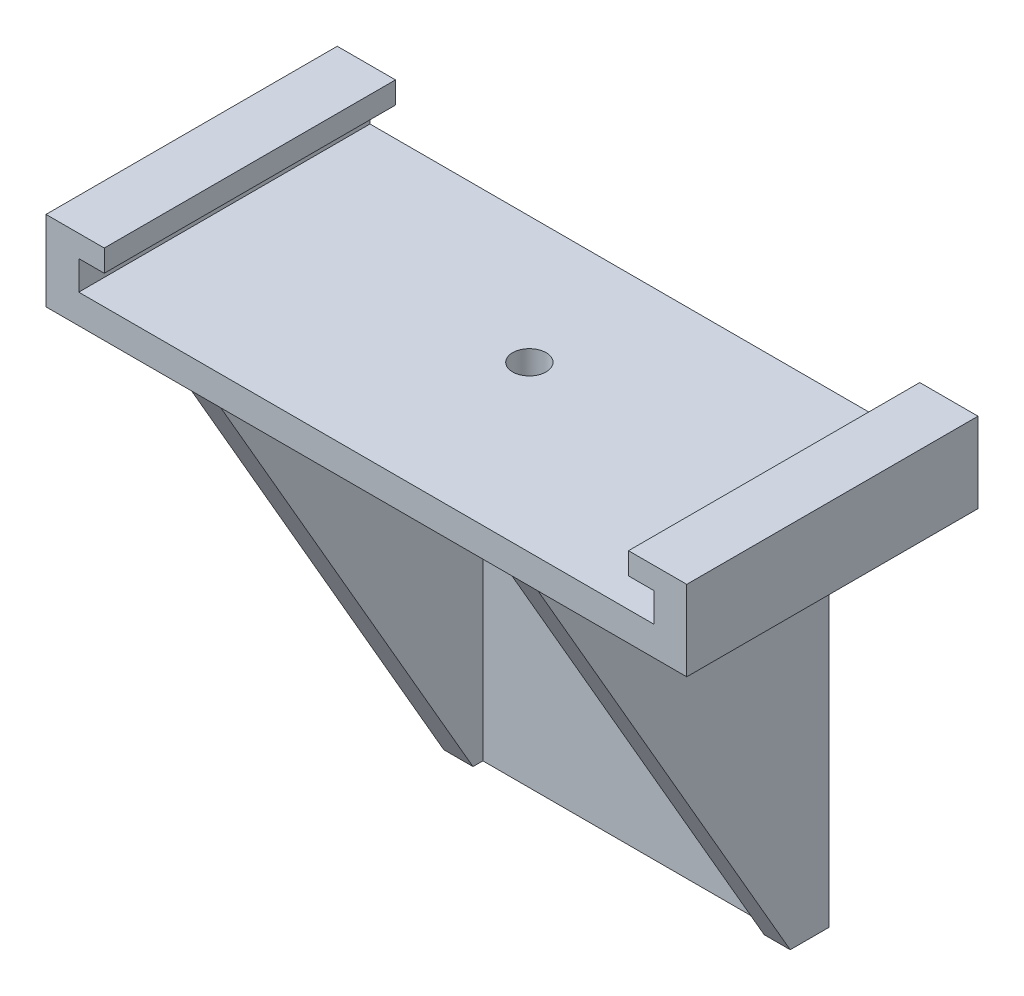
SolidWorks part; units mm, degrees
ref_plane "Front Plane" through (0, 0, 0) normal (0, 0, 1) x (1, 0, 0)
ref_plane "Top Plane" through (0, 0, 0) normal (0, 1, 0) x (1, 0, 0)
ref_plane "Right Plane" through (0, 0, 0) normal (1, 0, 0) x (0, 0, -1)
sketch "Sketch1" plane through (0, 0, 0) normal (0, 1, 0) x (1, 0, 0)
  line L1 (22, 10) -> (-22, 10)
  line L2 (22, 10) -> (22, -10)
  line L3 (22, -10) -> (-22, -10)
  line L4 (-22, 10) -> (-22, -10)
  line L5 (22, 10) -> (-22, -10) construction
  line L6 (22, -10) -> (-22, 10) construction
  point P0 (0, 0)
extrude "Boss-Extrude1" add sketch "Sketch1" along normal blind 2
sketch "Sketch2" plane through (0, 2, 0) normal (0, 1, 0) x (1, 0, 0)
  line L0 (-22, 10) -> (-19.75, 10)
  line L1 (22, 10) -> (-22, 10) construction
  line L2 (-19.75, 10) -> (-19.75, -10)
  line L3 (-22, -10) -> (22, -10) construction
  line L4 (-19.75, -10) -> (-22, -10)
  line L5 (-22, -10) -> (-22, 10)
  line L6 (22, 10) -> (19.75, 10)
  line L7 (19.75, 10) -> (19.75, -10)
  line L8 (19.75, -10) -> (22, -10)
  line L9 (22, -10) -> (22, 10) construction
  line L10 (22, -10) -> (22, 10)
extrude "Boss-Extrude2" add sketch "Sketch2" along normal blind 2
sketch "Sketch3" plane through (0, 4, 0) normal (0, 1, 0) x (1, 0, 0)
  line L0 (-22, 10) -> (-18, 10)
  line L1 (-18, 10) -> (-18, -10)
  line L2 (-19.75, -10) -> (19.75, -10) construction
  line L3 (-18, -10) -> (-22, -10)
  line L4 (-22, -10) -> (-22, 10)
  line L5 (22, 10) -> (18, 10)
  line L6 (19.75, 10) -> (-19.75, 10) construction
  line L7 (18, 10) -> (18, -10)
  line L8 (18, -10) -> (22, -10)
  line L9 (22, -10) -> (22, 10)
extrude "Boss-Extrude3" add sketch "Sketch3" along normal blind 1.5
sketch "Sketch7" plane through (0, 0, 0) normal (0, -1, 0) x (1, 0, 0)
  line L16 (-10, -10) -> (10, -10)
  line L17 (-10, 10) -> (-10, -10)
  line L18 (-10, -10) -> (-12, -10)
  line L19 (-12, -10) -> (-12, 10)
  line L20 (-12, 10) -> (-10, 10)
  line L21 (-10, -8) -> (-10, -10)
  line L22 (10, 10) -> (10, -10)
  line L23 (10, -10) -> (11.7847, -10)
  line L24 (11.7847, -10) -> (11.7847, 10)
  line L25 (11.7847, 10) -> (10, 10)
  line L26 (-10, -10) -> (-10, -8)
  line L27 (10, -8) -> (10, -10)
  line L28 (10, -10) -> (10, -8)
  line L29 (-10, -10) -> (-10, -8)
  line L30 (-10, -8) -> (10, -8)
  line L31 (10, -10) -> (10, -8)
  line M9 (-22, -10) -> (22, -10)
  line M11 (22, 10) -> (-22, 10)
  dimension "D1" = 2
extrude "Boss-Extrude4" add sketch "Sketch7" along normal blind 30 contours L19 L17 M9 M11 | L30 L17 L22 M9 | L24 L22 M9 M11
chamfer "Chamfer1" distance 30 angle 30 2 edges at (10.8923, -30, 10) (-11, -30, 10)
sketch "Sketch8" plane through (0, 0, 0) normal (0, -1, 0) x (1, 0, 0)
  circle A2 centre (-0.1077, -1.3) radius 1.15
  point P5 (-0.1077, -1.3)
extrude "Cut-Extrude1" cut sketch "Sketch8" against normal through all
